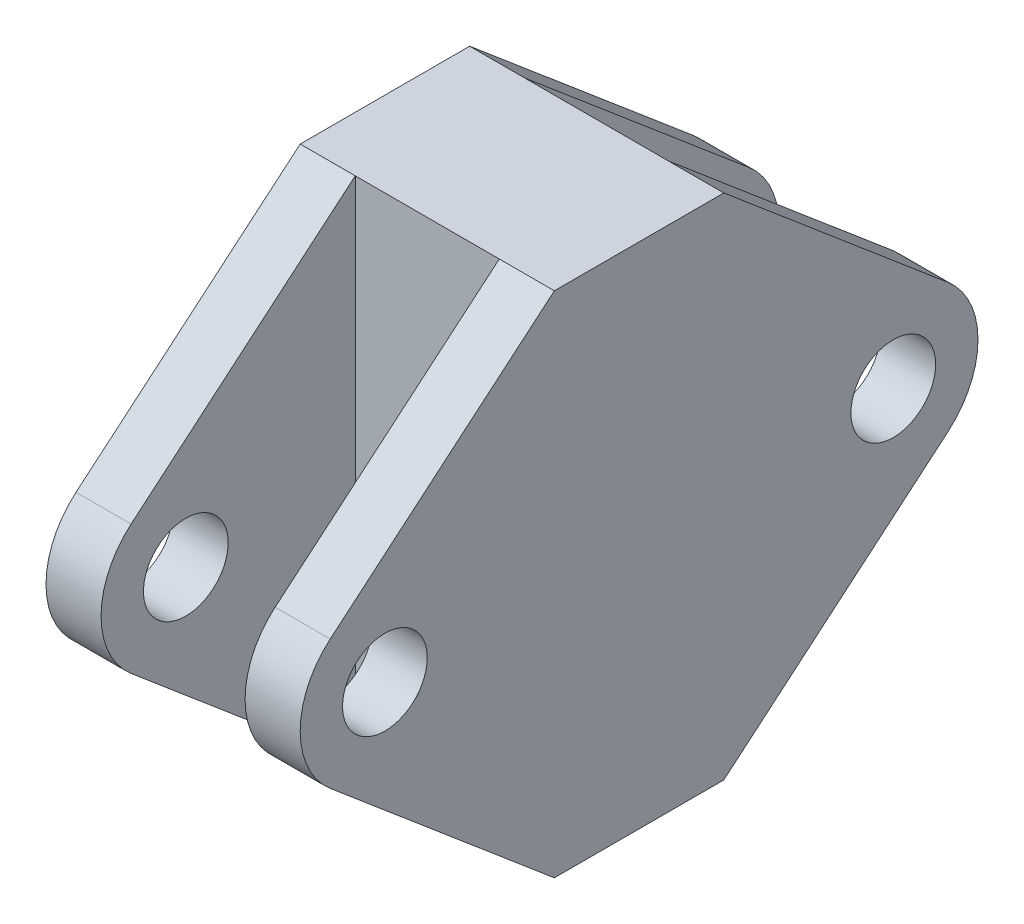
SolidWorks part; units mm, degrees
ref_plane "Front Plane" through (0, 0, 0) normal (0, 0, 1) x (1, 0, 0)
ref_plane "Top Plane" through (0, 0, 0) normal (0, 1, 0) x (1, 0, 0)
ref_plane "Right Plane" through (0, 0, 0) normal (1, 0, 0) x (0, 0, -1)
sketch "Sketch1" plane through (0, 0, 0) normal (1, 0, 0) x (0, 0, -1)
  line L0 (30, 0) -> (-30, 0) construction
  line L3 (-10, 30) -> (10, 30)
  line L6 (0, 30) -> (0, -30) construction
  line L10 (-10, 30) -> (-36.4556, 7.6371)
  line L11 (-75, 0) -> (-30, 0) construction
  line L12 (10, 30) -> (36.4556, 7.6371)
  line L13 (10, -30) -> (36.4556, -7.6371)
  line L14 (-10, -30) -> (-36.4556, -7.6371)
  line L15 (-10, -30) -> (10, -30)
  circle A0 centre (-30, 0) radius 5
  circle A1 centre (30, 0) radius 5
  arc A2 (-36.4556, 7.6371) -> (-36.4556, -7.6371) centre (-30, 0) ccw
  arc A3 (36.4556, 7.6371) -> (36.4556, -7.6371) centre (30, 0) cw
  point P7 (0, 0)
  point P13 (70, 0)
  point P18 (-70, 0)
  dimension "D2" = 10
  dimension "D4" = 10
  dimension "D1" = 30
  dimension "D3" = 30
  dimension "D6" = 10
extrude "Boss-Extrude1" add sketch "Sketch1" along normal mid plane 30
sketch "Sketch3" plane through (0, 0, 0) normal (1, 0, 0) x (0, 0, -1)
  line L0 (0, 30) -> (0, -50) construction
  line L1 (10, 30) -> (-10, 30) construction
  line L3 (-10, 30) -> (-40, 30)
  line L7 (-10, -30) -> (-10, 30)
  line L8 (-40, 30) -> (-40, -30)
  line L9 (-40, -30) -> (-10, -30)
  line L10 (-10, -30) -> (10, -30) construction
  line L15 (10, 30) -> (-10, 30) construction
  line L16 (40, -30) -> (10, -30)
  line L17 (40, 30) -> (40, -30)
  line L18 (10, -30) -> (10, 30)
  line L19 (10, 30) -> (40, 30)
  arc A1 (-36.4556, 7.6371) -> (-36.4556, -7.6371) centre (-30, 0) ccw construction
  point P6 (-30, 0)
  point P20 (30, 0)
extrude "Cut-Extrude2" cut sketch "Sketch3" against normal mid plane 17
